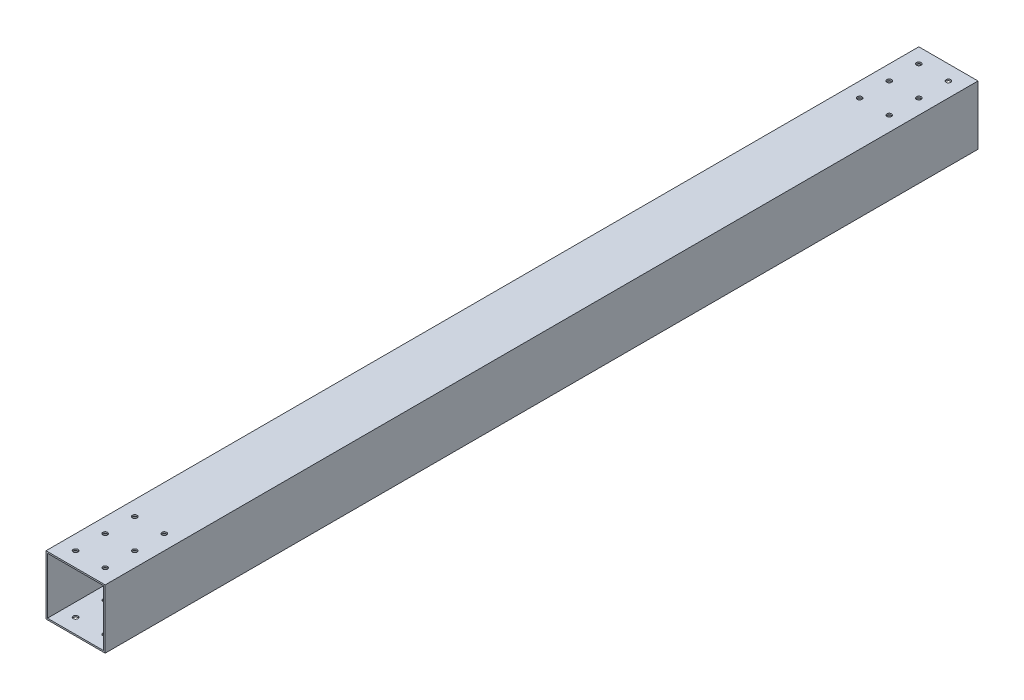
SolidWorks part; units mm, degrees
material "6061 合金"
ref_plane "前视基准面" through (0, 0, 0) normal (0, 0, 1) x (1, 0, 0)
ref_plane "上视基准面" through (0, 0, 0) normal (0, 1, 0) x (1, 0, 0)
ref_plane "右视基准面" through (0, 0, 0) normal (1, 0, 0) x (0, 0, -1)
other "Configuration Table"
sketch "草图1" plane through (0, 0, 0) normal (0, 0, 1) x (1, 0, 0)
  line L1 (-20, 20) -> (20, 20)
  line L2 (-20, 20) -> (-20, -20)
  line L3 (-20, -20) -> (20, -20)
  line L4 (20, 20) -> (20, -20)
  line L5 (-20, 20) -> (20, -20) construction
  line L6 (-20, -20) -> (20, 20) construction
  line L7 (-19, 19) -> (19, 19)
  line L8 (-19, 19) -> (-19, -19)
  line L9 (-19, -19) -> (19, -19)
  line L10 (19, 19) -> (19, -19)
  line L11 (-19, 19) -> (19, -19) construction
  line L12 (-19, -19) -> (19, 19) construction
  point P0 (0, 0)
  point P6 (0, 0)
  dimension "D1" = 40
  dimension "D2" = 1
extrude "凸台-拉伸1" add sketch "草图1" along normal mid plane 590
sketch "草图2" [suppressed] plane through (0, 20, 0) normal (0, 1, 0) x (1, 0, 0)
  line L0 (0, -290) -> (0, -50290) construction
  line L1 (20, -295) -> (-20, -295) construction
  line L2 (-10, -167.5) -> (-10, -147.5) construction
  line L3 (0, 0) -> (50000, 0) construction
  circle A0 centre (-10, -167.5) radius 1.6
  circle A1 centre (10, -167.5) radius 1.6
  circle A2 centre (-10, -147.5) radius 1.6
  circle A3 centre (10, -147.5) radius 1.6
  circle A4 centre (-10, -127.5) radius 1.6
  circle A5 centre (10, -127.5) radius 1.6
  circle A6 centre (-10, -107.5) radius 1.6
  circle A7 centre (10, -107.5) radius 1.6
  circle A8 centre (10, 107.5) radius 1.6
  circle A9 centre (-10, 107.5) radius 1.6
  circle A10 centre (10, 127.5) radius 1.6
  circle A11 centre (-10, 127.5) radius 1.6
  circle A12 centre (10, 147.5) radius 1.6
  circle A13 centre (-10, 147.5) radius 1.6
  circle A14 centre (10, 167.5) radius 1.6
  circle A15 centre (-10, 167.5) radius 1.6
  point P4 (0, -295)
  dimension "D1" = 20
  dimension "D2" = 3.2
  dimension "D3" = 107.5
  dimension "D5" = 20
  dimension "D4" = 4
sketch "草图3" plane through (0, 20, 0) normal (0, 1, 0) x (1, 0, 0)
  line L0 (-20, -295) -> (-20, 295) construction
  line L1 (20, -295) -> (-20, -295) construction
  line L2 (-10, -285) -> (10, -285) construction
  line L3 (-10, -265) -> (10, -265) construction
  line L4 (-10, -245) -> (10, -245) construction
  line L5 (-119.8039, 0) -> (300.0989, 0) construction
  line L6 (-10, 245) -> (10, 245) construction
  line L7 (-10, 265) -> (10, 265) construction
  line L8 (-10, 285) -> (10, 285) construction
  circle A0 centre (-10, 245) radius 1.6
  circle A1 centre (10, 245) radius 1.6
  circle A2 centre (10, 265) radius 1.6
  circle A3 centre (-10, 265) radius 1.6
  circle A4 centre (-10, 285) radius 1.6
  circle A5 centre (10, 285) radius 1.6
  circle A18 centre (10, -285) radius 1.6
  circle A19 centre (-10, -285) radius 1.6
  circle A20 centre (-10, -265) radius 1.6
  circle A21 centre (10, -265) radius 1.6
  circle A22 centre (10, -245) radius 1.6
  circle A23 centre (-10, -245) radius 1.6
  dimension "D1" = 20
  dimension "D2" = 20
  dimension "D3" = 20
  dimension "D4" = 10
  dimension "D5" = 20
  dimension "D6" = 20
  dimension "D7" = 10
  dimension "D8" = 10
  dimension "D9" = 10
  dimension "D10" = 3.2
  dimension "D11" = 3.2
  dimension "D12" = 3.2
  dimension "D13" = 3.2
  dimension "D14" = 3.2
  dimension "D15" = 3.2
extrude "切除-拉伸2" cut sketch "草图3" against normal blind 60
